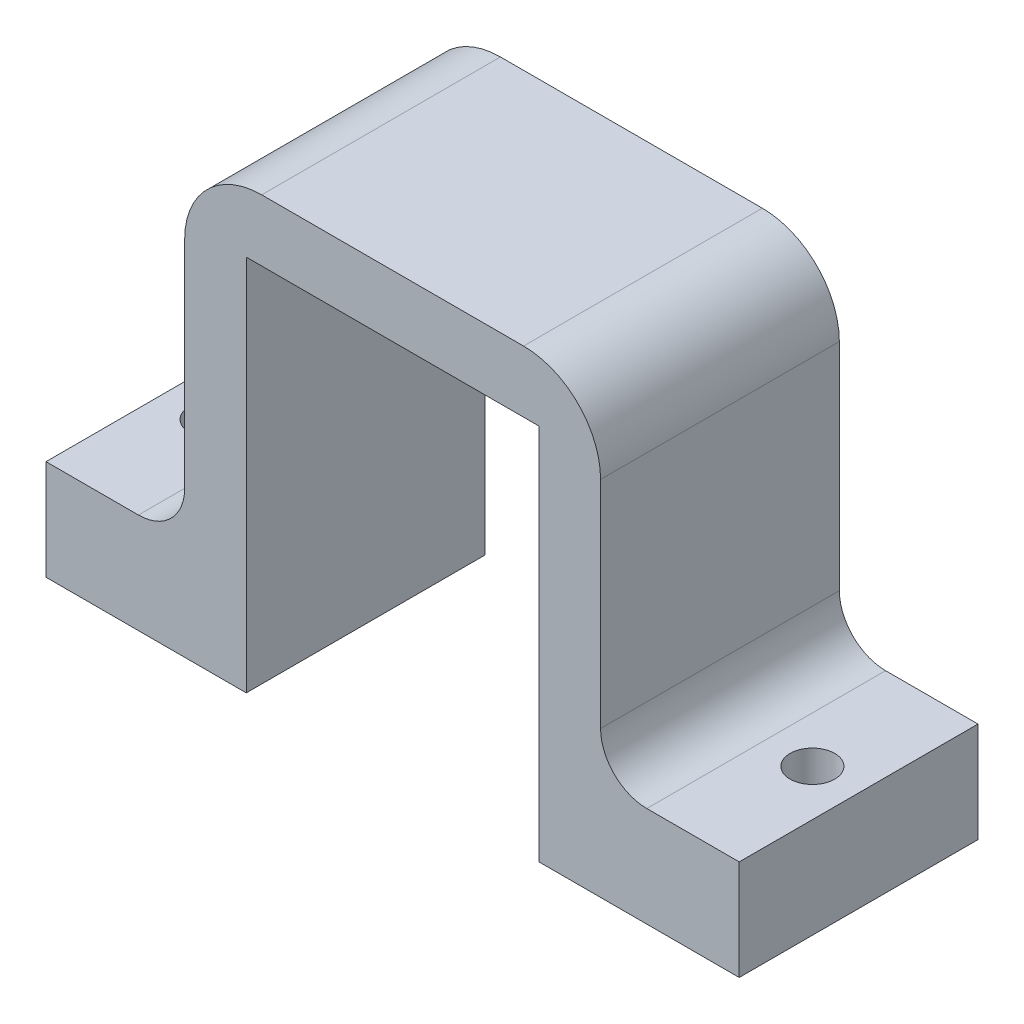
SolidWorks part; units mm, degrees
ref_plane "Front Plane" through (0, 0, 0) normal (0, 0, 1) x (1, 0, 0)
ref_plane "Top Plane" through (0, 0, 0) normal (0, 1, 0) x (1, 0, 0)
ref_plane "Right Plane" through (0, 0, 0) normal (1, 0, 0) x (0, 0, -1)
sketch "Sketch1" plane through (0, 0, 0) normal (0, 0, 1) x (1, 0, 0)
  line L0 (0, 3) -> (0, 17)
  line L1 (5, 22) -> (22, 22)
  line L2 (27, 17) -> (27, 3)
  line L3 (30, 0) -> (36, 0)
  line L4 (36, 0) -> (36, -4)
  line L5 (36, -4) -> (23, -4)
  line L6 (23, -4) -> (23, 18)
  line L7 (23, 18) -> (4, 18)
  line L8 (4, 18) -> (4, -4)
  line L9 (4, -4) -> (-9, -4)
  line L10 (-9, -4) -> (-9, 0)
  line L11 (-9, 0) -> (-3, 0)
  arc A0 (5, 22) -> (0, 17) centre (5, 17) ccw
  arc A1 (22, 22) -> (27, 17) centre (22, 17) cw
  arc A2 (0, 3) -> (-3, 0) centre (-3, 3) cw
  arc A3 (30, 0) -> (27, 3) centre (30, 3) cw
  point P18 (27, 22)
  point P21 (0, 0)
  dimension "D10" = 5
  dimension "D11" = 3
  dimension "D1" = 19
  dimension "D2" = 4
  dimension "D3" = 4
  dimension "D4" = 4
  dimension "D5" = 4
  dimension "D6" = 4
  dimension "D7" = 22
  dimension "D8" = 13
  dimension "D9" = 13
extrude "Boss-Extrude1" add sketch "Sketch1" along normal blind 23
ref_plane "Plane1" through (13.5, 0, 0) normal (1, 0, 0) x (0, 0, -1)
sketch "Sketch3" plane through (0, 0, 0) normal (0, 1, 0) x (1, 0, 0)
  line L0 (-9, -11.5) -> (36, -11.5) construction
  line L1 (-9, -23) -> (-9, 0) construction
  line L2 (36, -23) -> (36, 0) construction
  line L3 (13.5, -12.1) -> (13.5, 12.1) construction
  line L4 (36, 0) -> (30, 0) construction
  line L6 (36, -23) -> (30, -23) construction
  circle A0 centre (-6, -2.25) radius 1.45
  circle A1 centre (-6, -20.75) radius 1.45
  circle A2 centre (33, -20.75) radius 1.45
  circle A3 centre (33, -2.25) radius 1.45
  point P23 (33, -23)
  dimension "D1" = 2.9
  dimension "D2" = 2.25
  dimension "D3" = 2.25
sketch "Sketch4" plane through (0, 0, 0) normal (-1, 0, 0) x (0, 0, 1)
  line L0 (23, 17) -> (0, 17) construction
  line L1 (4, 17) -> (7.5, 17)
  line L2 (4, 17) -> (4, -4)
  line L3 (4, -4) -> (7.5, -4)
  line L4 (7.5, 17) -> (7.5, -4)
  line L5 (23, -4) -> (0, -4) construction
  line L7 (0, 0) -> (0, -4) construction
  dimension "D1" = 4
  dimension "D2" = 3.5
extrude "Cut-Extrude2" cut sketch "Sketch4" against normal blind 10 and the other way blind 23
sketch "Sketch5" plane through (0, 22, 0) normal (0, 1, 0) x (1, 0, 0)
  line L0 (-9, -7.5) -> (36, -7.5) construction
  line L1 (36, -23) -> (36, 0) construction
  line L3 (-9, 0) -> (36, 0)
  line L4 (-9, 0) -> (-9, -7.5)
  line L5 (-9, -7.5) -> (36, -7.5)
  line L6 (36, 0) -> (36, -7.5)
extrude "Cut-Extrude3" cut sketch "Sketch5" against normal blind 26
sketch "Sketch7" plane through (0, 0, 0) normal (0, 1, 0) x (1, 0, 0)
  line L0 (13.5, -8.525) -> (13.5, 8.525) construction
  line L3 (-3, -23) -> (-9, -23) construction
  line L5 (36, -7.5) -> (30, -7.5) construction
  circle A0 centre (-6, -15.25) radius 1.45
  circle A1 centre (33, -15.25) radius 1.45
  point P14 (-6, -23)
  dimension "D1" = 2.9
  dimension "D2" = 7.75
extrude "Cut-Extrude4" cut sketch "Sketch7" against normal blind 50
sketch "Sketch8" plane through (0, -4, 0) normal (0, -1, 0) x (1, 0, 0)
  line L0 (13.5, -8.525) -> (13.5, 8.525) construction
  line L1 (23, 23) -> (36, 23)
  line L2 (23, 23) -> (23, 7.5)
  line L3 (23, 7.5) -> (36, 7.5)
  line L4 (36, 23) -> (36, 7.5)
  line L5 (4, 7.5) -> (-9, 7.5)
  line L6 (-9, 23) -> (-9, 7.5)
  line L7 (4, 23) -> (-9, 23)
  line L8 (4, 23) -> (4, 7.5)
extrude "Boss-Extrude2" add sketch "Sketch8" along normal blind 2.5
sketch "Sketch9" plane through (0, -4, 0) normal (0, 1, 0) x (1, 0, 0)
  line L0 (13.5, -8.525) -> (13.5, 8.525) construction
  circle A0 centre (33, -15.25) radius 1.45
  circle A1 centre (-6, -15.25) radius 1.45
extrude "Cut-Extrude5" cut sketch "Sketch9" against normal blind 10
